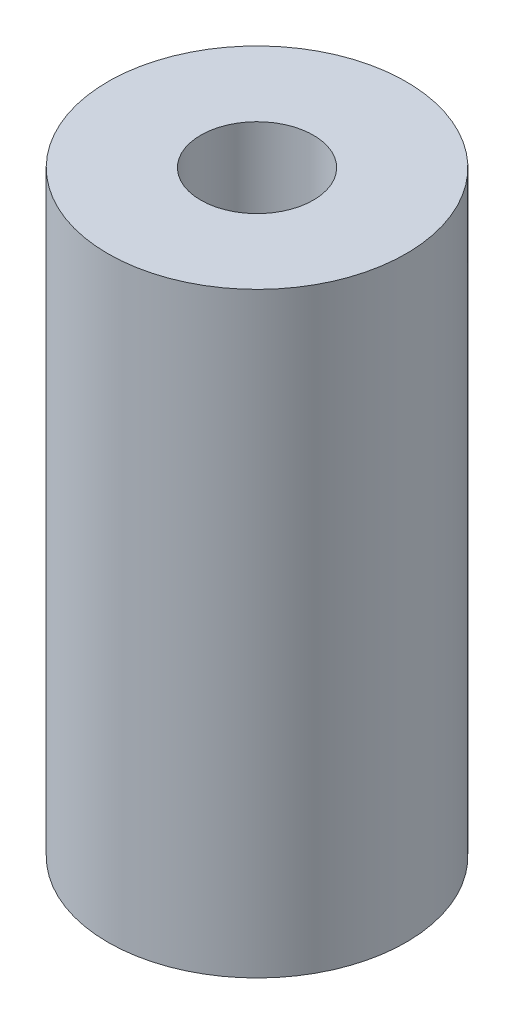
SolidWorks part; units mm, degrees
ref_plane "Front Plane" through (0, 0, 0) normal (0, 0, 1) x (1, 0, 0)
ref_plane "Top Plane" through (0, 0, 0) normal (0, 1, 0) x (1, 0, 0)
ref_plane "Right Plane" through (0, 0, 0) normal (1, 0, 0) x (0, 0, -1)
sketch "Sketch1" plane through (0, 0, 0) normal (0, 1, 0) x (1, 0, 0)
  circle A0 centre (0, 0) radius 4.5
  dimension "D1" = 9
extrude "Boss-Extrude1" add sketch "Sketch1" along normal blind 18
sketch "Sketch2" plane through (0, 18, 0) normal (0, 1, 0) x (1, 0, 0)
  circle A0 centre (0, 0) radius 1.7
  dimension "D1" = 3.4
extrude "Cut-Extrude1" cut sketch "Sketch2" against normal blind 8 contours A0
sketch "Sketch3" plane through (0, 0, 0) normal (0, -1, 0) x (1, 0, 0)
  circle A0 centre (0, 0) radius 2.5
  dimension "D1" = 5
extrude "Cut-Extrude2" cut sketch "Sketch3" against normal blind 8 contours A0
